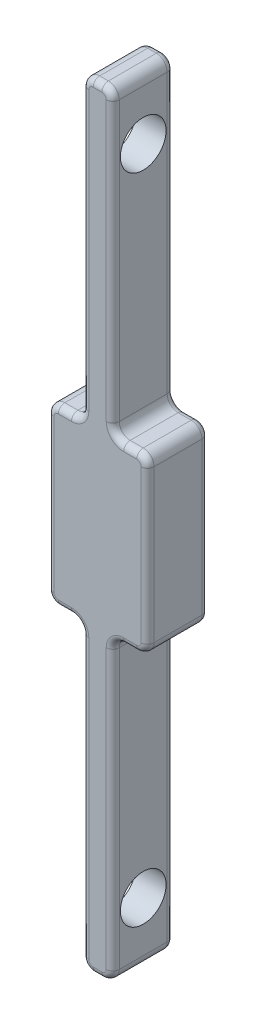
SolidWorks part; units mm, degrees
ref_plane "Front Plane" through (0, 0, 0) normal (1, 0, 0) x (0, 1, 0)
ref_plane "Top Plane" through (0, 0, 0) normal (0, 0, 1) x (0, 1, 0)
ref_plane "Right Plane" through (0, 0, 0) normal (0, 1, 0) x (-1, 0, 0)
sketch "Sketch4" plane through (0, 0, 0) normal (0, 0, 1) x (0, 1, 0)
  line L0 (-89, -3.5) -> (-89, 3.5)
  line L1 (-55, 0) -> (55, 0) construction
  line L2 (-89, 3.5) -> (-20, 3.5)
  line L3 (-20, 3.5) -> (-20, 11.5)
  line L4 (-20, 11.5) -> (20, 11.5)
  line L5 (20, 11.5) -> (20, 3.5)
  line L6 (20, 3.5) -> (89, 3.5)
  line L7 (89, 3.5) -> (89, -3.5)
  line L9 (0, -55) -> (0, 55) construction
  line L10 (20, -3.5) -> (89, -3.5)
  line L11 (20, -11.5) -> (20, -3.5)
  line L12 (-20, -11.5) -> (20, -11.5)
  line L13 (-20, -3.5) -> (-20, -11.5)
  line L14 (-89, -3.5) -> (-20, -3.5)
  dimension "D1" = 3.5
  dimension "D2" = 20
  dimension "D3" = 20
  dimension "D4" = 3.5
  dimension "D5" = 8
  dimension "D6" = 89
  dimension "D7" = 89
extrude "Boss-Extrude1" add sketch "Sketch4" along normal blind 14
sketch "Sketch5" plane through (3.5, 0, 0) normal (1, 0, 0) x (0, 1, 0)
  line L0 (-89, 7) -> (89, 7) construction
  line L1 (-89, 14) -> (-89, 0) construction
  line L2 (89, 14) -> (89, 0) construction
  line L3 (0, -7.7) -> (0, 7.7) construction
  circle A0 centre (75, 7) radius 5.25
  circle A1 centre (-75, 7) radius 5.25
  dimension "D1" = 10.5
  dimension "D2" = 75
  dimension "D3" = 75
extrude "Cut-Extrude1" cut sketch "Sketch5" against normal through all
sketch "Sketch6" plane through (0, 0, 0) normal (0, 0, -1) x (1, 0, 0)
  line L0 (-2.5, -2.5904) -> (-2.5, -3.6)
  line L1 (-2.5, -3.6) -> (-2, -15.6)
  line L2 (2, -15.6) -> (2.5, -3.6)
  line L3 (2.5, -3.6) -> (2.5, -2.5904)
  line L4 (2.9933, -2) -> (6.6, -2)
  line L5 (6.6, 2) -> (2.9933, 2)
  line L6 (2.5, 2.5904) -> (2.5, 3.6)
  line L7 (2.5, 3.6) -> (2, 15.6)
  line L8 (-2, 15.6) -> (-2.5, 3.6)
  line L9 (-2.5, 3.6) -> (-2.5, 2.5904)
  line L10 (-2.9933, 2) -> (-6.6, 2)
  line L11 (-6.6, -2) -> (-2.9933, -2)
  line L12 (-7.7, 0) -> (7.7, 0) construction
  line L13 (-2.5, -2.5904) -> (-2.5, -3.6)
  line L14 (-2.5, -3.6) -> (-2, -15.6)
  line L15 (2, -15.6) -> (2.5, -3.6)
  line L16 (2.5, -3.6) -> (2.5, -2.5904)
  line L17 (2.9933, -2) -> (6.6, -2)
  line L18 (6.6, 2) -> (2.9933, 2)
  line L19 (2.5, 2.5904) -> (2.5, 3.6)
  line L20 (2.5, 3.6) -> (2, 15.6)
  line L21 (-2, 15.6) -> (-2.5, 3.6)
  line L22 (-2.5, 3.6) -> (-2.5, 2.5904)
  line L23 (-2.9933, 2) -> (-6.6, 2)
  line L24 (-6.6, -2) -> (-2.9933, -2)
  arc A0 (-2, -15.6) -> (2, -15.6) centre (0, -15.6) ccw
  arc A1 (2.5, -2.5904) -> (2.9933, -2) centre (0, 0) ccw
  arc A2 (6.6, -2) -> (6.6, 2) centre (6.6, 0) ccw
  arc A3 (2.9933, 2) -> (2.5, 2.5904) centre (0, 0) ccw
  arc A4 (2, 15.6) -> (-2, 15.6) centre (0, 15.6) ccw
  arc A5 (-2.5, 2.5904) -> (-2.9933, 2) centre (0, 0) ccw
  arc A6 (-6.6, 2) -> (-6.6, -2) centre (-6.6, 0) ccw
  arc A7 (-2.9933, -2) -> (-2.5, -2.5904) centre (0, 0) ccw
  arc A8 (-2, -15.6) -> (2, -15.6) centre (0, -15.6) ccw
  arc A9 (2.5, -2.5904) -> (2.9933, -2) centre (0, 0) ccw
  arc A10 (6.6, -2) -> (6.6, 2) centre (6.6, 0) ccw
  arc A11 (2.9933, 2) -> (2.5, 2.5904) centre (0, 0) ccw
  arc A12 (2, 15.6) -> (-2, 15.6) centre (0, 15.6) ccw
  arc A13 (-2.5, 2.5904) -> (-2.9933, 2) centre (0, 0) ccw
  arc A14 (-6.6, 2) -> (-6.6, -2) centre (-6.6, 0) ccw
  arc A15 (-2.9933, -2) -> (-2.5, -2.5904) centre (0, 0) ccw
  circle A16 centre (0, -15.6) radius 0.675
  circle A17 centre (0, -13.4) radius 0.675
  circle A18 centre (0, -11.2) radius 0.675
  circle A19 centre (0, -9) radius 0.675
  circle A20 centre (0, -6.8) radius 0.675
  circle A21 centre (0, -4.6) radius 0.675
  circle A22 centre (-6.6, 0) radius 0.6
  circle A23 centre (-4.6, 0) radius 0.6
  circle A24 centre (6.6, 0) radius 0.6
  circle A25 centre (4.6, 0) radius 0.6
  circle A26 centre (0, 4.6) radius 0.675
  circle A27 centre (0, 6.8) radius 0.675
  circle A28 centre (0, 9) radius 0.675
  circle A29 centre (0, 11.2) radius 0.675
  circle A30 centre (0, 13.4) radius 0.675
  circle A31 centre (0, 15.6) radius 0.675
  point P28 (0, 0)
  point P30 (0, 17.6)
  point P33 (0, -17.6)
  point P34 (-8.6, 0)
  point P91 (0, 0)
  point P92 (0, 0)
  dimension "D1" = 17.6
  dimension "D2" = 17.6
  dimension "D3" = 8.6
sketch "Sketch8" plane through (0, 0, 0) normal (0, 0, -1) x (1, 0, 0)
  line L12 (6.6, 2) -> (2.9933, 2)
  line L13 (2.9933, -2) -> (6.6, -2)
  line L14 (2.5, -3.6) -> (2.5, -2.5904)
  line L15 (2, -15.6) -> (2.5, -3.6)
  line L16 (-2.5, -3.6) -> (-2, -15.6)
  line L17 (-2.5, -2.5904) -> (-2.5, -3.6)
  line L18 (-6.6, -2) -> (-2.9933, -2)
  line L19 (-2.9933, 2) -> (-6.6, 2)
  line L20 (-2.5, 3.6) -> (-2.5, 2.5904)
  line L21 (-2, 15.6) -> (-2.5, 3.6)
  line L22 (2.5, 3.6) -> (2, 15.6)
  line L23 (2.5, 2.5904) -> (2.5, 3.6)
  line L24 (6.6, 2) -> (2.9933, 2)
  line L25 (2.9933, -2) -> (6.6, -2)
  line L26 (2.5, -3.6) -> (2.5, -2.5904)
  line L27 (2, -15.6) -> (2.5, -3.6)
  line L28 (-2.5, -3.6) -> (-2, -15.6)
  line L29 (-2.5, -2.5904) -> (-2.5, -3.6)
  line L30 (-6.6, -2) -> (-2.9933, -2)
  line L31 (-2.9933, 2) -> (-6.6, 2)
  line L32 (-2.5, 3.6) -> (-2.5, 2.5904)
  line L35 (2.5, 2.5904) -> (2.5, 3.6)
  line L36 (-2.9933, 2) -> (-6.6, 2)
  line L37 (-6.6, -2) -> (-2.9933, -2)
  line L38 (-2.5, -2.5904) -> (-2.5, -3.6)
  line L39 (-2.5, -3.6) -> (-2, -15.6)
  line L40 (2, -15.6) -> (2.5, -3.6)
  line L41 (2.5, -3.6) -> (2.5, -2.5904)
  line L42 (2.9933, -2) -> (6.6, -2)
  line L43 (6.6, 2) -> (2.9933, 2)
  line L44 (2.5, 2.5904) -> (2.5, 3.6)
  line L45 (2.5, 3.6) -> (2, 15.6)
  line L46 (-2, 15.6) -> (-2.5, 3.6)
  line L47 (-2.5, 3.6) -> (-2.5, 2.5904)
  line L48 (-2.9933, 2) -> (-6.6, 2)
  line L49 (-6.6, -2) -> (-2.9933, -2)
  line L50 (-2.5, -2.5904) -> (-2.5, -3.6)
  line L51 (-2.5, -3.6) -> (-2, -15.6)
  line L52 (2, -15.6) -> (2.5, -3.6)
  line L53 (2.5, -3.6) -> (2.5, -2.5904)
  line L54 (2.9933, -2) -> (6.6, -2)
  line L55 (6.6, 2) -> (2.9933, 2)
  line L56 (2.5, 2.5904) -> (2.5, 3.6)
  line L57 (2.5, 3.6) -> (2, 15.6)
  line L58 (-2, 15.6) -> (-2.5, 3.6)
  line L59 (-2.5, 3.6) -> (-2.5, 2.5904)
  arc A8 (6.6, -2) -> (6.6, 2) centre (6.6, 0) ccw
  arc A9 (2.5, -2.5904) -> (2.9933, -2) centre (0, 0) ccw
  arc A10 (-2, -15.6) -> (2, -15.6) centre (0, -15.6) ccw
  arc A11 (-2.9933, -2) -> (-2.5, -2.5904) centre (0, 0) ccw
  arc A12 (-6.6, 2) -> (-6.6, -2) centre (-6.6, 0) ccw
  arc A13 (-2.5, 2.5904) -> (-2.9933, 2) centre (0, 0) ccw
  arc A14 (2, 15.6) -> (-2, 15.6) centre (0, 15.6) ccw
  arc A15 (2.9933, 2) -> (2.5, 2.5904) centre (0, 0) ccw
  arc A16 (6.6, -2) -> (6.6, 2) centre (6.6, 0) ccw
  arc A17 (2.5, -2.5904) -> (2.9933, -2) centre (0, 0) ccw
  arc A18 (-2, -15.6) -> (2, -15.6) centre (0, -15.6) ccw
  arc A19 (-2.9933, -2) -> (-2.5, -2.5904) centre (0, 0) ccw
  arc A20 (-6.6, 2) -> (-6.6, -2) centre (-6.6, 0) ccw
  arc A21 (-2.5, 2.5904) -> (-2.9933, 2) centre (0, 0) ccw
  arc A23 (2.9933, 2) -> (2.5, 2.5904) centre (0, 0) ccw
  arc A34 (-6.6, 2) -> (-6.6, -2) centre (-6.6, 0) ccw
  arc A35 (-2.9933, -2) -> (-2.5, -2.5904) centre (0, 0) ccw
  arc A36 (-2, -15.6) -> (2, -15.6) centre (0, -15.6) ccw
  arc A37 (2.5, -2.5904) -> (2.9933, -2) centre (0, 0) ccw
  arc A38 (6.6, -2) -> (6.6, 2) centre (6.6, 0) ccw
  arc A39 (2.9933, 2) -> (2.5, 2.5904) centre (0, 0) ccw
  arc A40 (2, 15.6) -> (-2, 15.6) centre (0, 15.6) ccw
  arc A41 (-2.5, 2.5904) -> (-2.9933, 2) centre (0, 0) ccw
  arc A42 (-6.6, 2) -> (-6.6, -2) centre (-6.6, 0) ccw
  arc A43 (-2.9933, -2) -> (-2.5, -2.5904) centre (0, 0) ccw
  arc A44 (-2, -15.6) -> (2, -15.6) centre (0, -15.6) ccw
  arc A45 (2.5, -2.5904) -> (2.9933, -2) centre (0, 0) ccw
  arc A46 (6.6, -2) -> (6.6, 2) centre (6.6, 0) ccw
  arc A47 (2.9933, 2) -> (2.5, 2.5904) centre (0, 0) ccw
  arc A48 (2, 15.6) -> (-2, 15.6) centre (0, 15.6) ccw
  arc A49 (-2.5, 2.5904) -> (-2.9933, 2) centre (0, 0) ccw
  dimension "D1" = 0
  dimension "D7" = 0
extrude "Cut-Extrude3" cut sketch "Sketch8" against normal blind 1.4 contours L57 A48 L58 L32 A21 L31 A20 L30 A19 L29 L28 A18 L27 L26 A17 L25 A16 L24 A23 L35
sketch "Sketch9" plane through (0, 0, 1.4) normal (0, 0, -1) x (1, 0, 0)
  circle A0 centre (0, -15.6) radius 0.675 construction
  circle A1 centre (0, -13.4) radius 0.675 construction
  circle A2 centre (0, -11.2) radius 0.675 construction
  circle A3 centre (0, -9) radius 0.675 construction
  circle A4 centre (0, -6.8) radius 0.675 construction
  circle A5 centre (0, -4.6) radius 0.675 construction
  circle A6 centre (-6.6, 0) radius 0.6 construction
  circle A7 centre (-4.6, 0) radius 0.6 construction
  circle A8 centre (6.6, 0) radius 0.6 construction
  circle A9 centre (4.6, 0) radius 0.6 construction
  circle A10 centre (0, 4.6) radius 0.675 construction
  circle A11 centre (0, 6.8) radius 0.675 construction
  circle A12 centre (0, 9) radius 0.675 construction
  circle A13 centre (0, 11.2) radius 0.675 construction
  circle A14 centre (0, 13.4) radius 0.675 construction
  circle A15 centre (0, 15.6) radius 0.675 construction
  circle A16 centre (0, -15.6) radius 0.675
  circle A17 centre (0, -13.4) radius 0.675
  circle A18 centre (0, -11.2) radius 0.675
  circle A19 centre (0, -9) radius 0.675
  circle A20 centre (0, -6.8) radius 0.675
  circle A21 centre (0, -4.6) radius 0.675
  circle A22 centre (-6.6, 0) radius 0.6
  circle A23 centre (-4.6, 0) radius 0.6
  circle A24 centre (6.6, 0) radius 0.6
  circle A25 centre (4.6, 0) radius 0.6
  circle A26 centre (0, 4.6) radius 0.675
  circle A27 centre (0, 6.8) radius 0.675
  circle A28 centre (0, 9) radius 0.675
  circle A29 centre (0, 11.2) radius 0.675
  circle A30 centre (0, 13.4) radius 0.675
  circle A31 centre (0, 15.6) radius 0.675
  circle A32 centre (0, 15.6) radius 0.575
  circle A33 centre (0, 13.4) radius 0.575
  circle A34 centre (0, 11.2) radius 0.575
  circle A35 centre (0, 9) radius 0.575
  circle A36 centre (0, 6.8) radius 0.575
  circle A37 centre (0, 4.6) radius 0.575
  circle A38 centre (4.6, 0) radius 0.5
  circle A39 centre (6.6, 0) radius 0.5
  circle A40 centre (-4.6, 0) radius 0.5
  circle A41 centre (-6.6, 0) radius 0.5
  circle A42 centre (0, -4.6) radius 0.575
  circle A43 centre (0, -6.8) radius 0.575
  circle A44 centre (0, -9) radius 0.575
  circle A45 centre (0, -11.2) radius 0.575
  circle A46 centre (0, -13.4) radius 0.575
  circle A47 centre (0, -15.6) radius 0.575
  point P80 (0, 0)
  dimension "D1" = 1.35
  dimension "D2" = 0.1
extrude "Cut-Extrude5" cut sketch "Sketch9" against normal blind 8 contours A33 | A34 | A35 | A36 | A37 | A41 | A40 | A38 | A39 | A42 | A43 | A44 | A45 | A46 | A47 | A32
fillet "Fillet1" radius 2.5 12 edges at (3.5, -20, 7) (11.5, -20, 7) (11.5, 20, 7) (-3.5, -89, 7) (3.5, -89, 7) (-3.5, 89, 7) (3.5, 89, 7) (-11.5, -20, 7) (-3.5, -20, 7) (-11.5, 20, 7) (-3.5, 20, 7) (3.5, 20, 7)
fillet "Fillet2" radius 1.5 24 edges at (-10.7678, 19.2678, 14) (-7.5, 20, 14) (-4.2322, 20.7322, 14) (-3.5, 54.5, 14) (-2.7678, 88.2678, 14) (0, 89, 14) (2.7678, 88.2678, 14) (3.5, 54.5, 14) (4.2322, 20.7322, 14) (7.5, 20, 14) (10.7678, 19.2678, 14) (11.5, 0, 14) (10.7678, -19.2678, 14) (7.5, -20, 14) (4.2322, -20.7322, 14) (3.5, -54.5, 14) (2.7678, -88.2678, 14) (0, -89, 14) (-2.7678, -88.2678, 14) (-3.5, -54.5, 14) (-4.2322, -20.7322, 14) (-7.5, -20, 14) (-10.7678, -19.2678, 14) (-11.5, 0, 14)
fillet "Fillet3" radius 1.5 24 edges at (10.7678, -19.2678, 0) (7.5, -20, 0) (4.2322, -20.7322, 0) (3.5, -54.5, 0) (2.7678, -88.2678, 0) (0, -89, 0) (-2.7678, -88.2678, 0) (-3.5, -54.5, 0) (-4.2322, -20.7322, 0) (-7.5, -20, 0) (-10.7678, -19.2678, 0) (-11.5, 0, 0) (-10.7678, 19.2678, 0) (-7.5, 20, 0) (-4.2322, 20.7322, 0) (-3.5, 54.5, 0) (-2.7678, 88.2678, 0) (0, 89, 0) (2.7678, 88.2678, 0) (3.5, 54.5, 0) (4.2322, 20.7322, 0) (7.5, 20, 0) (10.7678, 19.2678, 0) (11.5, 0, 0)
